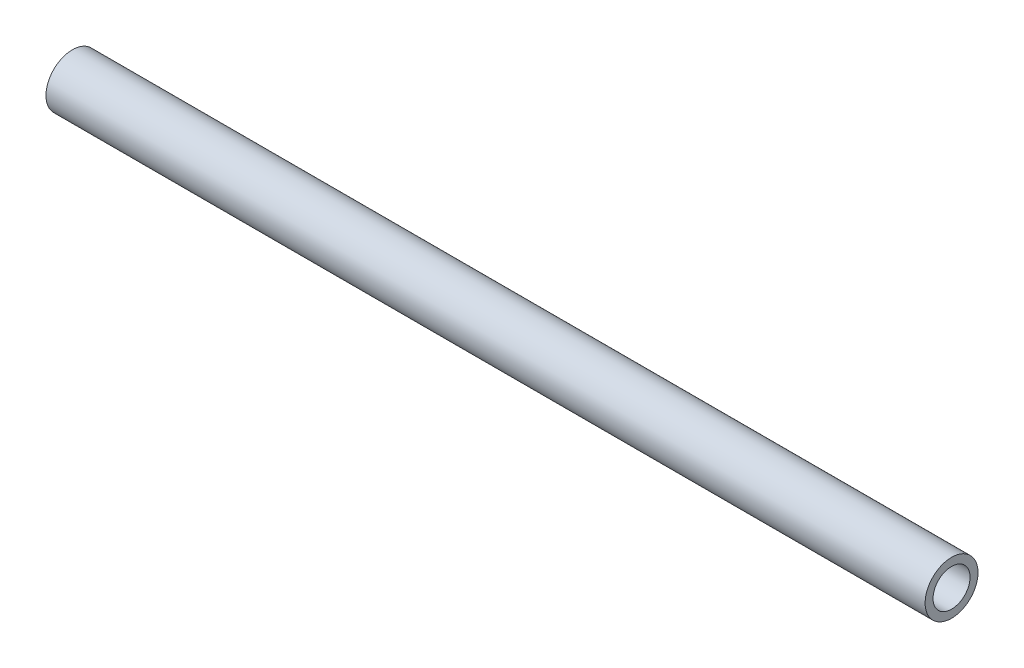
SolidWorks part; units mm, degrees
material "AISI 4130 Steel, annealed at 865C"
ref_plane "Front Plane" through (0, 0, 0) normal (0, 0, 1) x (1, 0, 0)
ref_plane "Top Plane" through (0, 0, 0) normal (0, 1, 0) x (1, 0, 0)
ref_plane "Right Plane" through (0, 0, 0) normal (1, 0, 0) x (0, 0, -1)
sketch "Sketch1" plane through (0, 0, 0) normal (0, 0, 1) x (1, 0, 0)
  line L0 (265.225, 0) -> (-265.225, 0) construction
  line L2 (-166.2135, 10) -> (166.2135, 10)
  line L4 (-166.2135, 10) -> (-166.2135, 7)
  line L5 (-166.2135, 7) -> (166.2135, 7)
  line L6 (166.2135, 7) -> (166.2135, 10)
  line L7 (0, 0) -> (0, 10) construction
  point P4 (0, 0)
  point P9 (0, 7)
  point P14 (197.9352, 0)
  point P15 (-197.9352, 0)
  dimension "D2" = 20
  dimension "D1" = 14
  dimension "D3" = 395.8704
  dimension "D4" = 31.7217
revolve "Revolve1" add sketch "Sketch1" angle 360 about L0
equation "\"CA_ID\"= 14"
equation "\"D1@Sketch1\"=\"CA_ID\""
equation "\"tube_end_to_ball_center\" = 31.721675mm"
equation "\"D4@Sketch1\"=\"tube_end_to_ball_center\""
